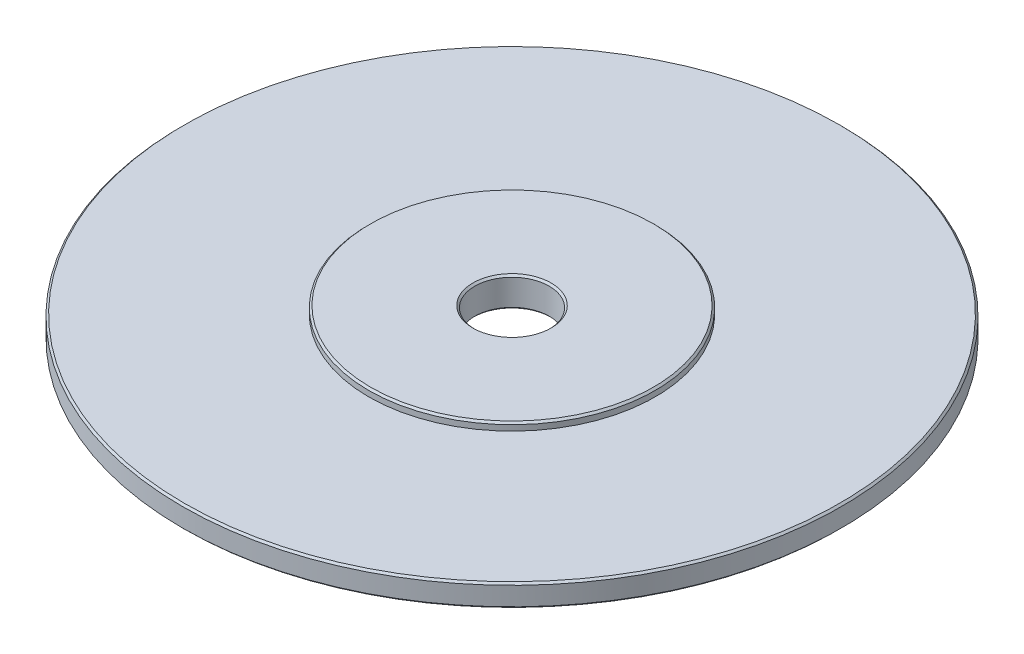
SolidWorks part; units mm, degrees
material "POM 乙缩醛共聚物"
ref_plane "前视基准面" through (0, 0, 0) normal (0, 0, 1) x (1, 0, 0)
ref_plane "上视基准面" through (0, 0, 0) normal (0, 1, 0) x (1, 0, 0)
ref_plane "右视基准面" through (0, 0, 0) normal (1, 0, 0) x (0, 0, -1)
sketch "草图2" plane through (0, 0, 0) normal (1, 0, 0) x (0, 0, -1)
  line L0 (10, 0) -> (88.5, 0)
  line L1 (88.5, 0) -> (88.5, 6)
  line L2 (88.5, 6) -> (38.5, 6)
  line L3 (38.5, 6) -> (38.5, 8)
  line L4 (38.5, 8) -> (10, 8)
  line L5 (10, 8) -> (10, 0)
  line L6 (0, 0) -> (0, 76.2211) construction
  dimension "D1" = 6
  dimension "D2" = 38.5
  dimension "D3" = 2
  dimension "D4" = 50
  dimension "D5" = 10
revolve "旋转1" add sketch "草图2" angle 360 about L6
chamfer "倒角1" distance 0.5 angle 45 5 edges at (0, 0, -88.5) (0, 6, -88.5) (0, 8, -10) (0, 0, -10) (0, 8, -38.5)
